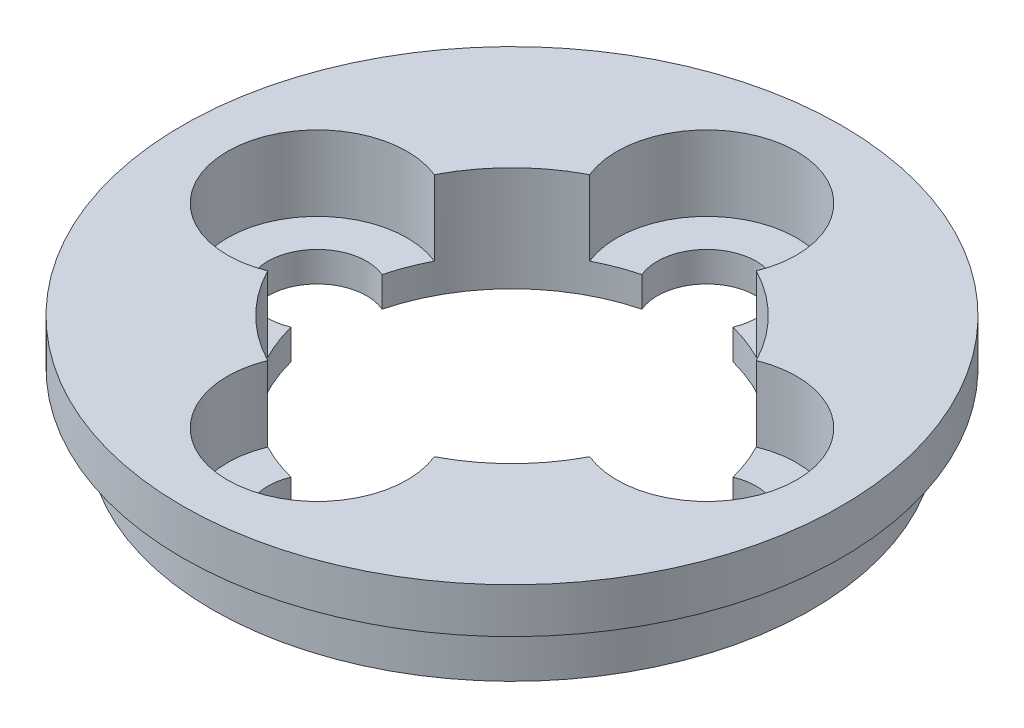
SolidWorks part; units mm, degrees
ref_plane "前视基准面" through (0, 0, 0) normal (0, 0, 1) x (1, 0, 0)
ref_plane "上视基准面" through (0, 0, 0) normal (0, 1, 0) x (1, 0, 0)
ref_plane "右视基准面" through (0, 0, 0) normal (1, 0, 0) x (0, 0, -1)
sketch "草图1" plane through (0, 0, 0) normal (0, 1, 0) x (1, 0, 0)
  circle A0 centre (0, 0) radius 6.05
  circle A1 centre (0, 0) radius 10
  dimension "D1" = 12.1
  dimension "D2" = 20
extrude "凸台-拉伸1" add sketch "草图1" along normal blind 2
sketch "草图2" plane through (0, 2, 0) normal (0, 1, 0) x (1, 0, 0)
  circle A0 centre (0, 0) radius 6.5
  circle A1 centre (-6.5, 0) radius 1.65
  circle M2 centre (0, 0) radius 6.05
  dimension "D1" = 13
  dimension "D2" = 3.3
extrude "切除-拉伸1" cut sketch "草图2" against normal blind 2 contours A0 A1 | A1 M2 | A0 A1 M2
pattern_circular "阵列(圆周)1" count 4 over 360 about axis through (0, 0, 0) along (0, 1, 0) of "切除-拉伸1"
sketch "草图3" plane through (0, 2, 0) normal (0, 1, 0) x (1, 0, 0)
  circle A0 centre (0, 0) radius 11
  circle A1 centre (0, 0) radius 10 construction
  arc M1 (1.5192, -5.8562) -> (-1.5192, -5.8562) centre (0, -6.5) cw
  arc M2 (-1.5192, -5.8562) -> (-5.8562, -1.5192) centre (0, 0) cw
  arc M3 (-5.8562, -1.5192) -> (-5.8562, 1.5192) centre (-6.5, 0) cw
  arc M4 (-5.8562, 1.5192) -> (-1.5192, 5.8562) centre (0, 0) cw
  arc M5 (-1.5192, 5.8562) -> (1.5192, 5.8562) centre (0, 6.5) cw
  arc M6 (1.5192, 5.8562) -> (5.8562, 1.5192) centre (0, 0) cw
  arc M7 (5.8562, 1.5192) -> (5.8562, -1.5192) centre (6.5, 0) cw
  arc M8 (5.8562, -1.5192) -> (1.5192, -5.8562) centre (0, 0) cw
  circle M9 centre (0, 0) radius 10
  dimension "D1" = 1
extrude "凸台-拉伸2" add sketch "草图3" along normal blind 1.5 contours M9 M8 M1 M2 M3 M4 M5 M6 M7 | A0 M9
sketch "草图4" plane through (0, 3.5, 0) normal (0, 1, 0) x (1, 0, 0)
  circle A0 centre (-6.5, 0) radius 3
  dimension "D1" = 6
extrude "切除-拉伸2" cut sketch "草图4" against normal blind 2.5
pattern_circular "阵列(圆周)2" count 4 over 360 about axis through (0, 0, 0) along (0, 1, 0) of "切除-拉伸2"
